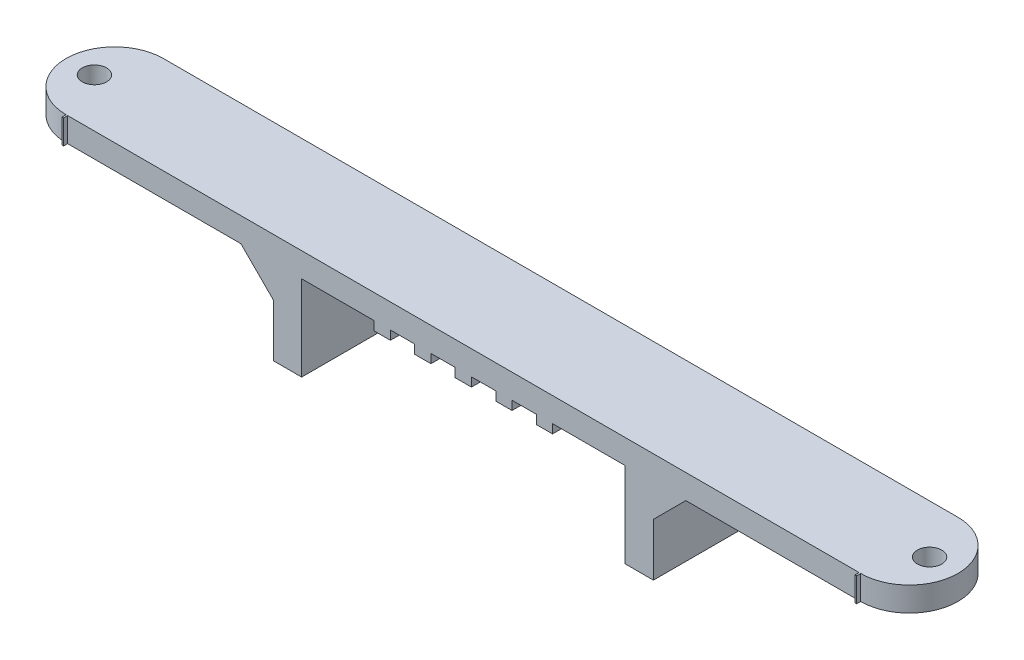
SolidWorks part; units mm, degrees
ref_plane "Front Plane" through (0, 0, 0) normal (0, 0, 1) x (1, 0, 0)
ref_plane "Top Plane" through (0, 0, 0) normal (0, 1, 0) x (1, 0, 0)
ref_plane "Right Plane" through (0, 0, 0) normal (1, 0, 0) x (0, 0, -1)
sketch "Sketch1" plane through (0, 0, 0) normal (0, 1, 0) x (1, 0, 0)
  line L0 (-49, 0) -> (49, 0) construction
  line L1 (-49, 6) -> (49, 6)
  line L2 (-49, -6) -> (49, -6)
  arc A0 (-49, 6) -> (-49, -6) centre (-49, 0) ccw
  arc A1 (49, -6) -> (49, 6) centre (49, 0) ccw
  circle A2 centre (-51.5, 0) radius 1.5
  circle A3 centre (51.5, 0) radius 1.5
  point P2 (0, 0)
  point P12 (-55, 0)
  point P13 (55, 0)
  dimension "D3" = 3
  dimension "D4" = 3.5
  dimension "D1" = 110
  dimension "D2" = 12
  dimension "D5" = 3.5
extrude "Boss-Extrude1" add sketch "Sketch1" along normal blind 3 contours L2 A1 L1 A0 | A2 | A3
sketch "Sketch4" plane through (0, 0, 0) normal (0, -1, 0) x (1, 0, 0)
  line L0 (-19.94, 6) -> (-19.94, -6)
  line L1 (-49, 6) -> (49, 6) construction
  line L2 (-49, -6) -> (49, -6) construction
  line L3 (-19.94, -6) -> (-23.44, -6)
  line L4 (-23.44, -6) -> (-23.44, 6)
  line L5 (-23.44, 6) -> (-19.94, 6)
  line L6 (0, 6) -> (0, -6) construction
  line L7 (-19.94, 5.075) -> (-19.94, -14.3256) construction
  line L8 (23.44, -6) -> (23.44, 6)
  line L9 (19.94, -6) -> (23.44, -6)
  line L10 (19.94, 6) -> (19.94, -6)
  line L11 (23.44, 6) -> (19.94, 6)
  dimension "D1" = 0
  dimension "D2" = 3.5
extrude "Boss-Extrude3" add sketch "Sketch4" along normal blind 10.5
sketch "Sketch5" plane through (0, 0, 0) normal (0, -1, 0) x (1, 0, 0)
  line L1 (4, 6) -> (4, -6)
  line L2 (4, 6) -> (6, 6)
  line L6 (-19.94, -6) -> (19.94, -6) construction
  line L7 (-1, 6) -> (1, 6)
  line L8 (-1, 6) -> (-1, -6)
  line L9 (-1, -6) -> (1, -6)
  line L10 (1, 6) -> (1, -6)
  line L11 (-1, 6) -> (1, -6) construction
  line L12 (-1, -6) -> (1, 6) construction
  line L13 (6, 6) -> (6, -6)
  line L14 (4, -6) -> (6, -6)
  line L15 (9, 6) -> (9, -6)
  line L16 (9, 6) -> (11, 6)
  line L17 (11, 6) -> (11, -6)
  line L18 (9, -6) -> (11, -6)
  line L19 (-4, 6) -> (-4, -6)
  line L20 (-6, -6) -> (-4, -6)
  line L21 (-6, 6) -> (-6, -6)
  line L22 (-6, 6) -> (-4, 6)
  line L23 (-9, 6) -> (-9, -6)
  line L24 (-11, -6) -> (-9, -6)
  line L25 (-11, 6) -> (-11, -6)
  line L26 (-11, 6) -> (-9, 6)
  point P0 (0, 0)
  dimension "D1" = 2
  dimension "D2" = 3
  dimension "D3" = 3
extrude "Boss-Extrude4" add sketch "Sketch5" along normal blind 1.1
sketch "Sketch6" plane through (0, 0, 6) normal (0, 0, 1) x (1, 0, 0)
  line L0 (49, 0) -> (49, 3)
  line L1 (49, 3) -> (48.8, 3)
  line L2 (-49, 3) -> (49, 3) construction
  line L3 (48.8, 3) -> (48.8, 0)
  line L4 (23.44, 0) -> (49, 0) construction
  line L5 (48.8, 0) -> (49, 0)
  line L6 (0, 0) -> (0, 3) construction
  line L7 (-48.8, 0) -> (-49, 0)
  line L8 (-48.8, 3) -> (-48.8, 0)
  line L9 (-49, 3) -> (-48.8, 3)
  line L10 (-49, 0) -> (-49, 3)
  dimension "D1" = 0.2
extrude "Boss-Extrude5" add sketch "Sketch6" along normal blind 0.5 contours L0 L1 L3 L5 | L8 L7 L10 L9
chamfer "Chamfer1" distance 4 2 edges at (-23.44, 0, 0) (23.44, 0, 0)
